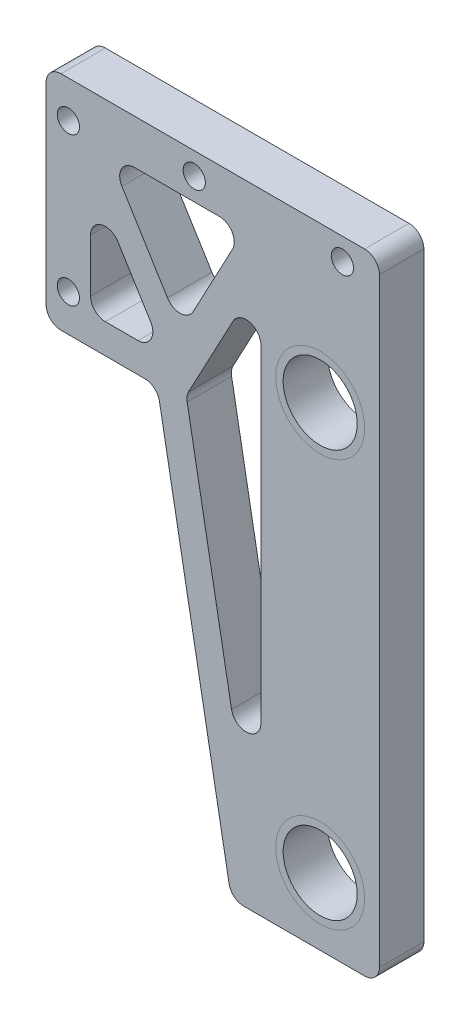
SolidWorks part; units mm, degrees
material "Thornel Mat VMA"
ref_plane "前视基准面" through (0, 0, 0) normal (0, 0, 1) x (1, 0, 0)
ref_plane "上视基准面" through (0, 0, 0) normal (0, 1, 0) x (1, 0, 0)
ref_plane "右视基准面" through (0, 0, 0) normal (1, 0, 0) x (0, 0, -1)
other "Configuration Table"
sketch "草图1" plane through (0, 0, 0) normal (0, 0, 1) x (1, 0, 0)
  line L0 (0, 0) -> (0, -55) construction
  line L1 (-37, 20.95) -> (8, 20.95)
  line L2 (8, 20.95) -> (8, -64.05)
  line L3 (8, -64.05) -> (-12, -64.05)
  line L4 (-12, -64.05) -> (-22, -9.05)
  line L5 (-22, -9.05) -> (-37, -9.05)
  line L6 (-37, -9.05) -> (-37, 20.95)
  line L7 (-17, 17.95) -> (3, 17.95) construction
  line L8 (-34, 15.95) -> (-34, -4.05) construction
  circle A0 centre (0, 0) radius 6
  circle A1 centre (0, -55) radius 6
  circle A2 centre (3, 17.95) radius 1.5
  circle A3 centre (-17, 17.95) radius 1.5
  circle A4 centre (-34, 15.95) radius 1.5
  circle A5 centre (-34, -4.05) radius 1.5
  dimension "D1" = 12
  dimension "D4" = 20.95
  dimension "D10" = 3
  dimension "D12" = 5
  dimension "D13" = 5
  dimension "D2" = 55
  dimension "D3" = 8
  dimension "D5" = 45
  dimension "D6" = 20
  dimension "D7" = 15
  dimension "D8" = 85
  dimension "D9" = 30
  dimension "D11" = 20
  dimension "D14" = 3
  dimension "D15" = 3
extrude "凸台-拉伸1" add sketch "草图1" along normal blind 6
sketch "草图2" plane through (0, 0, 6) normal (0, 0, 1) x (1, 0, 0)
  circle A0 centre (0, 0) radius 5
  circle A1 centre (0, -55) radius 5
  circle A2 centre (0, -55) radius 6 construction
  circle A3 centre (0, 0) radius 6 construction
  circle A4 centre (0, -55) radius 6
  circle A5 centre (0, 0) radius 6
  dimension "D1" = 10
extrude "凸台-拉伸2" add sketch "草图2" against normal blind 6 separate body
sketch "草图3" plane through (0, 0, 6) normal (0, 0, 1) x (1, 0, 0)
  line L0 (-8, 14.95) -> (-8, -63.6893)
  line L1 (-8, -63.6893) -> (-18.6617, -5.05)
  line L2 (-18.6617, -5.05) -> (-31, -5.05)
  line L3 (-31, -5.05) -> (-31, 14.95)
  line L4 (-31, 14.95) -> (-8, 14.95)
  line L5 (8, 20.95) -> (-37, 20.95) construction
  line L6 (-37, 20.95) -> (-37, -9.05) construction
  line L7 (-37, -9.05) -> (-22, -9.05) construction
  line L8 (-22, -9.05) -> (-12, -64.05) construction
  line L9 (-18.6617, -5.05) -> (-8, 14.95) construction
  line L10 (-18.6617, -5.05) -> (-31, 14.95) construction
  line L11 (-31, 11.1408) -> (-21.0117, -5.05)
  line L12 (-28.65, 14.95) -> (-18.7882, -1.0357)
  line L13 (-18.7882, -1.0357) -> (-10.2664, 14.95)
  line L14 (-8, 10.6985) -> (-18.0853, -8.2203)
  circle A0 centre (0, 0) radius 6 construction
  dimension "D1" = 6
  dimension "D2" = 6
  dimension "D3" = 4
  dimension "D4" = 4
  dimension "D5" = 8
  dimension "D6" = 2
  dimension "D7" = 2
  dimension "D8" = 2
  dimension "D9" = 2
extrude "切除-拉伸1" cut sketch "草图3" against normal up to surface (6 mm away) contours L0 L14 L1 | L12 L13 L4 | L11 L3 L2 up to face at (-32.5, 15.95, 0)
fillet "圆角2" radius 2 15 edges at (-31, 11.1408, 3) (-31, -5.05, 3) (-21.0117, -5.05, 3) (-8, -63.6893, 3) (-8, 10.6985, 3) (-18.0853, -8.2203, 3) (8, -64.05, 3) (-22, -9.05, 3) (-37, -9.05, 3) (-37, 20.95, 3) (8, 20.95, 3) (-28.65, 14.95, 3) (-18.7882, -1.0357, 3) (-10.2664, 14.95, 3) (-12, -64.05, 3)
sketch "草图4" plane through (0, 0, 6) normal (0, 0, 1) x (1, 0, 0)
  circle A0 centre (0, 0) radius 8
  circle A1 centre (0, 0) radius 5
  circle A2 centre (0, -55) radius 5
  circle A3 centre (0, -55) radius 8
  dimension "D1" = 10
  dimension "D2" = 16
extrude "凸台-拉伸3" add sketch "草图4" along normal blind 0.5 separate body
sketch "草图5" plane through (0, 0, 0) normal (0, 0, -1) x (-1, 0, 0)
  circle A0 centre (0, -55) radius 8 construction
  circle A1 centre (0, 0) radius 8 construction
  circle A2 centre (0, -55) radius 8
  circle A3 centre (0, 0) radius 8
  circle A4 centre (0, -55) radius 5 construction
  circle A5 centre (0, 0) radius 5 construction
  circle A6 centre (0, -55) radius 5
  circle A7 centre (0, 0) radius 5
extrude "凸台-拉伸4" add sketch "草图5" along normal blind 0.5 separate body
delete or keep bodies "实体-删除/保留 1" type delete bodies bodies 111 112 113 114
